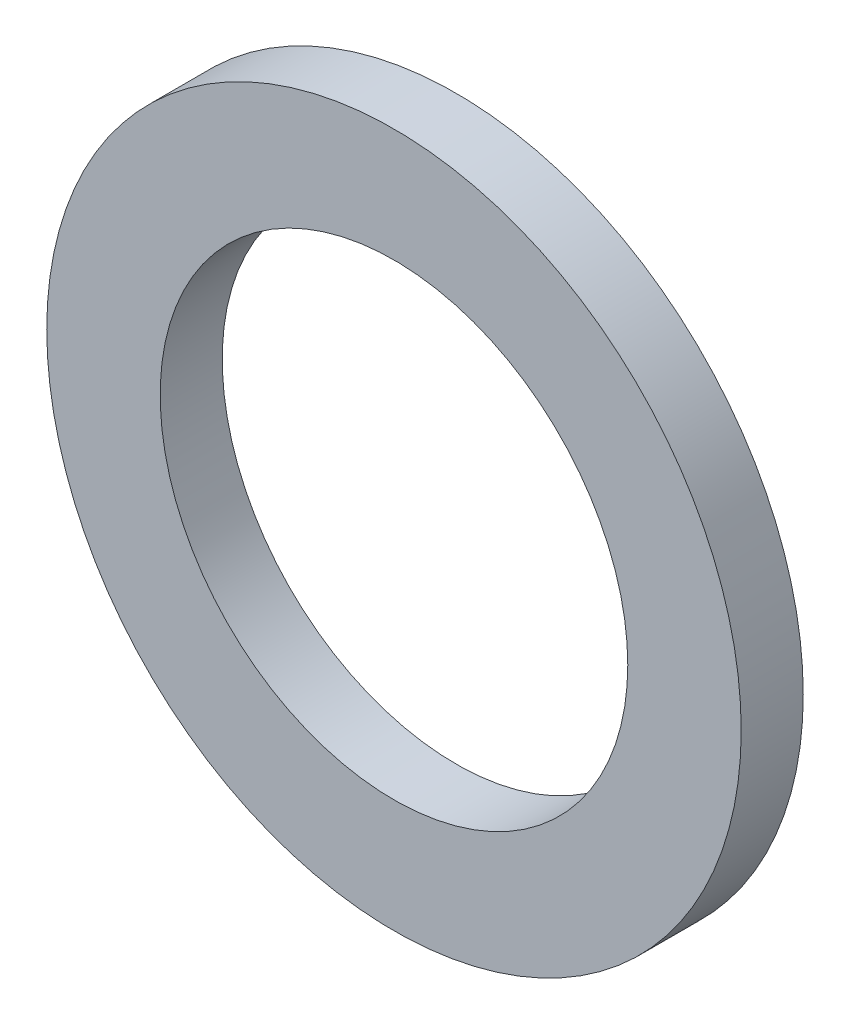
SolidWorks part; units mm, degrees
ref_plane "Front Plane" through (0, 0, 0) normal (0, 0, 1) x (1, 0, 0)
ref_plane "Top Plane" through (0, 0, 0) normal (0, 1, 0) x (1, 0, 0)
ref_plane "Right Plane" through (0, 0, 0) normal (1, 0, 0) x (0, 0, -1)
sketch "Sketch1" plane through (0, 0, 0) normal (0, 0, 1) x (1, 0, 0)
  circle A0 centre (0, 0) radius 9.525
  circle A1 centre (0, 0) radius 6.4135
  point P5 (0, -9.525)
  dimension "OD" = 19.05
  dimension "ID" = 12.827
sketch "Sketch2" plane through (0, 0, 0) normal (1, 0, 0) x (0, 0, -1)
  line L0 (-0.8509, 0) -> (0.8509, 0) construction
  point P0 (-0.8509, -9.525)
  point P4 (0, 0)
  point P6 (0.8509, -9.525)
  dimension "Thickness Range" = 1.7018
sketch "Sketch3" plane through (0, 0, 0) normal (0, 0, 1) x (1, 0, 0)
  circle A0 centre (0, 0) radius 9.525 construction
  circle A1 centre (0, 0) radius 6.4135 construction
  circle A2 centre (0, 0) radius 9.525
  circle A3 centre (0, 0) radius 6.4135
extrude "Boss-Extrude1" add sketch "Sketch3" along normal up to vertex (0.8509 mm away) and the other way up to vertex (0.8509 mm away) up to point (0, -9.525, 0.8509) other way up to point (0, -9.525, -0.8509)
